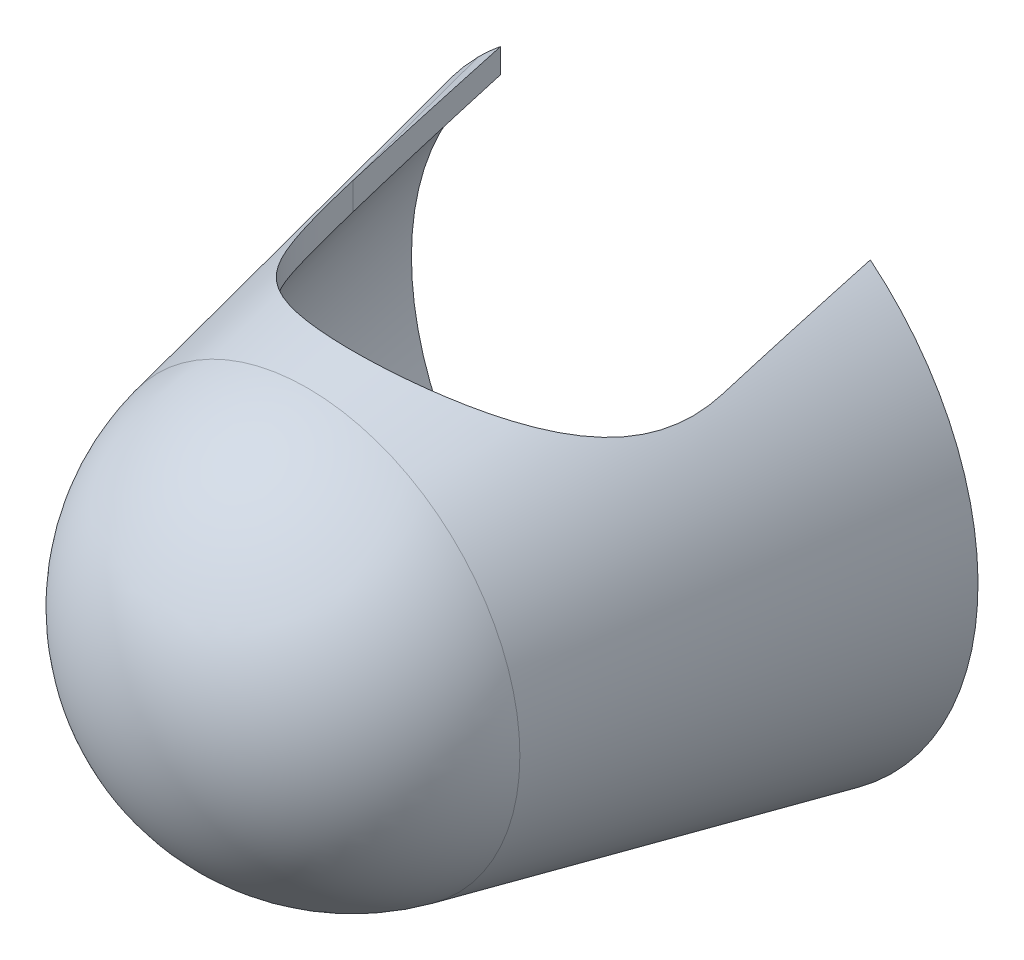
SolidWorks part; units mm, degrees
ref_plane "Ebene vorne" through (0, 0, 0) normal (0, 0, 1) x (1, 0, 0)
ref_plane "Ebene oben" through (0, 0, 0) normal (0, 1, 0) x (1, 0, 0)
ref_plane "Ebene rechts" through (0, 0, 0) normal (1, 0, 0) x (0, 0, -1)
sketch "Skizze1" plane through (0, 0, 0) normal (1, 0, 0) x (0, 0, -1)
  line L0 (400, -791.3009) -> (400, 0) construction
  line L1 (-500, 500) -> (500, 500) construction
  line L2 (-500, 500) -> (-500, -500) construction
  line L3 (-500, -500) -> (500, -500) construction
  line L4 (500, 500) -> (500, -500) construction
  line L6 (400, -791.3009) -> (-622.021, -574.0636)
  line L7 (-500, 0) -> (-500, -550)
  line L8 (-500, -550) -> (400, -741.3009)
  line L9 (0, 0) -> (-1460.7907, 0) construction
  line L10 (0, 0) -> (4818.5589, 0) construction
  line L11 (-1086.8886, 0) -> (-500, 0)
  line L12 (400, -741.3009) -> (400, -791.3009)
  arc A1 (-622.021, -574.0636) -> (-1086.8886, 0) centre (-500, 0) cw
  point P8 (0, 500)
  point P16 (500, 0)
  dimension "D1" = 1000
  dimension "D2" = 1000
  dimension "D3" = 50
  dimension "D6" = 50
  dimension "D7" = 12
  dimension "D8" = 100
  dimension "D9" = 12
revolve "Rotation1" add sketch "Skizze1" angle 360 about L10
sketch "Skizze2" plane through (0, 0, 0) normal (0, 1, 0) x (1, 0, 0)
  line L0 (-500, 0) -> (-500, 400)
  line L1 (741.3009, 400) -> (-741.3009, 400) construction
  line L2 (-500, 400) -> (500, 400)
  line L3 (500, 400) -> (500, 0)
  arc A1 (-500, 0) -> (500, 0) centre (0, 0) ccw
  dimension "D1" = 500
extrude "Schnitt-Linear austragen1" cut sketch "Skizze2" along normal through all contours L2 L3 A1 L0
